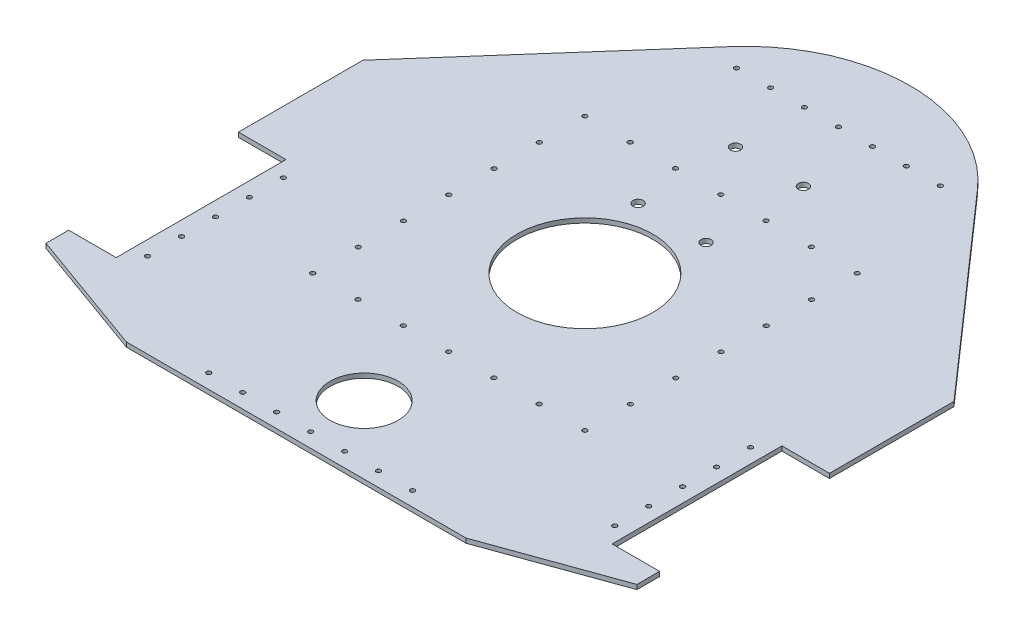
SolidWorks part; units mm, degrees
ref_plane "Front Plane" through (0, 0, 0) normal (0, 0, 1) x (1, 0, 0)
ref_plane "Top Plane" through (0, 0, 0) normal (0, 1, 0) x (1, 0, 0)
ref_plane "Right Plane" through (0, 0, 0) normal (1, 0, 0) x (0, 0, -1)
sketch "Sketch1" plane through (0, 0, 0) normal (0, 1, 0) x (1, 0, 0)
  line L0 (-240, -25) -> (240, -25) construction
  line L1 (240, -25) -> (0, 215) construction
  line L2 (0, 215) -> (-240, -25) construction
  line L3 (0, 215) -> (0, -25) construction
  line L6 (-219, 50) -> (-219, -100)
  line L7 (-219, -100) -> (-261, -100)
  line L8 (-261, -100) -> (-261, -120)
  line L10 (-150, -160) -> (150, -160)
  line L11 (-219, 50) -> (-261, 50)
  line L12 (-261, 50) -> (-261, 160)
  line L13 (-261, 160) -> (-110, 331.6587)
  line L14 (-150, -160) -> (-261, -120)
  line L15 (261, 160) -> (110, 331.6587)
  line L16 (150, -160) -> (261, -120)
  line L18 (261, -100) -> (261, -120)
  line L19 (219, -100) -> (261, -100)
  line L20 (219, 50) -> (219, -100)
  line L21 (219, 50) -> (261, 50)
  line L22 (261, 50) -> (261, 160)
  arc A7 (110, 331.6587) -> (-110, 331.6587) centre (0, 237.0979) ccw
  point P29 (0, 331.6587)
  dimension "D1" = 480
  dimension "D4" = 75
  dimension "D6" = 20
  dimension "D7" = 42
  dimension "D2" = 240
  dimension "D3" = 21
  dimension "D5" = 75
  dimension "D8" = 20
  dimension "D9" = 21
  dimension "D10" = 21
  dimension "D11" = 110
  dimension "D12" = 110
  dimension "D13" = 150
  dimension "D14" = 42
  dimension "D15" = 300
extrude "Boss-Extrude1" add sketch "Sketch1" along normal blind 4
sketch "Sketch2" plane through (0, 4, 0) normal (0, 1, 0) x (1, 0, 0)
  line L0 (-206.3, 24.3269) -> (-206.3, -74.3269) construction
  line L1 (-219, 50) -> (-219, -100) construction
  line L2 (0, 319.1541) -> (0, -121.9152) construction
  line L4 (-219, 50) -> (-261, 50) construction
  line L5 (219, 50) -> (261, 50) construction
  circle A0 centre (-206.3, -25) radius 2
  circle A1 centre (-206.3, 5) radius 2
  circle A2 centre (-206.3, 35) radius 2
  circle A3 centre (-206.3, -55) radius 2
  circle A4 centre (-206.3, -85) radius 2
  circle A6 centre (206.3, -85) radius 2
  circle A7 centre (206.3, -55) radius 2
  circle A8 centre (206.3, -25) radius 2
  circle A9 centre (206.3, 5) radius 2
  circle A10 centre (206.3, 35) radius 2
  dimension "D2" = 3
  dimension "D1" = 12.7
  dimension "D4" = 75
  dimension "D5" = 75
  dimension "D6" = 12.7
  dimension "D3" = 3
extrude "Cut-Extrude1" cut sketch "Sketch2" against normal up to surface (4 mm away) up to face at (0, 0, -17.1134)
sketch "Sketch4" plane through (0, 4, 0) normal (0, 1, 0) x (1, 0, 0)
  line L0 (0, 0) -> (0, -135) construction
  line L1 (-120.2082, 215.2082) -> (-120.2082, -25.2082) construction
  line L2 (-219, -25) -> (219, -25) construction
  line L7 (-219, 50) -> (-219, -100) construction
  line L8 (219, 50) -> (219, -100) construction
  line L9 (-150, -160) -> (150, -160) construction
  line L10 (0, 382.1556) -> (0, -160) construction
  line L11 (0, 95) -> (-120.2082, 215.2082) construction
  circle A5 centre (0, -100) radius 30
  arc A6 (110, 331.6587) -> (-110, 331.6587) centre (0, 237.0979) ccw construction
  circle A7 centre (-120.2082, 215.2082) radius 2
  circle A8 centre (0, 95) radius 60
  circle A9 centre (120.2082, 215.2082) radius 2
  circle A10 centre (120.2082, -25.2082) radius 2
  circle A11 centre (-120.2082, -25.2082) radius 2
  circle A12 centre (-120.2082, 95) radius 2
  circle A13 centre (-120.2082, 135) radius 2
  circle A14 centre (-120.2082, 175) radius 2
  circle A15 centre (-120.2082, 55) radius 2
  circle A16 centre (-120.2082, 15) radius 2
  circle A17 centre (120.2082, 15) radius 2
  circle A18 centre (120.2082, 55) radius 2
  circle A19 centre (120.2082, 95) radius 2
  circle A20 centre (120.2082, 135) radius 2
  circle A21 centre (120.2082, 175) radius 2
  circle A22 centre (-80.2082, 215.2082) radius 2
  circle A23 centre (-80.2082, -25.2082) radius 2
  circle A24 centre (-40.2082, 215.2082) radius 2
  circle A25 centre (-40.2082, -25.2082) radius 2
  circle A26 centre (-0.2082, 215.2082) radius 2
  circle A27 centre (-0.2082, -25.2082) radius 2
  circle A28 centre (39.7918, 215.2082) radius 2
  circle A29 centre (39.7918, -25.2082) radius 2
  circle A30 centre (79.7918, 215.2082) radius 2
  circle A31 centre (79.7918, -25.2082) radius 2
  point P31 (0, 95)
  dimension "D1" = 120
  dimension "D4" = 60
  dimension "D7" = 3
  dimension "D3" = 45
  dimension "D5" = 60
  dimension "D2" = 170
  dimension "D8" = 3
  dimension "D9" = 6
  dimension "D6" = 4
extrude "Cut-Extrude2" cut sketch "Sketch4" against normal up to surface (4 mm away) up to face at (-206.3, 0, -3)
sketch "Sketch5" plane through (0, 4, 0) normal (0, 1, 0) x (1, 0, 0)
  line L0 (-219, -25) -> (219, -25) construction
  line L1 (-219, 50) -> (-219, -100) construction
  line L2 (219, 50) -> (219, -100) construction
  line L3 (0, 0) -> (0, 215) construction
  circle A0 centre (-30, 172) radius 4.5
  circle A1 centre (30, 172) radius 4.5
  circle A2 centre (30, 258) radius 4.5
  circle A3 centre (-30, 258) radius 4.5
  dimension "D2" = 30
  dimension "D1" = 215
  dimension "D3" = 43
  dimension "D4" = 2
  dimension "D5" = 2
extrude "Cut-Extrude3" cut sketch "Sketch5" against normal up to surface (4 mm away) up to face at (-80.2082, 0, -213.2082)
sketch "Sketch6" plane through (0, 4, 0) normal (0, 1, 0) x (1, 0, 0)
  line L0 (-110, 331.6587) -> (110, 331.6587) construction
  line L1 (0, 331.6587) -> (0, 301.6408) construction
  line L2 (0, -135) -> (0, -101.3263) construction
  line L4 (-150, -160) -> (150, -160) construction
  circle A0 centre (0, 318.9587) radius 2
  circle A1 centre (30, 318.9587) radius 2
  circle A2 centre (60, 318.9587) radius 2
  circle A3 centre (90, 318.9587) radius 2
  circle A4 centre (-30, 318.9587) radius 2
  circle A5 centre (-60, 318.9587) radius 2
  circle A6 centre (-90, 318.9587) radius 2
  circle A7 centre (0, -147.3) radius 2
  circle A8 centre (30, -147.3) radius 2
  circle A9 centre (60, -147.3) radius 2
  circle A10 centre (90, -147.3) radius 2
  circle A11 centre (-30, -147.3) radius 2
  circle A12 centre (-60, -147.3) radius 2
  circle A13 centre (-90, -147.3) radius 2
  dimension "D1" = 12.7
  dimension "D4" = 12.7
  dimension "D2" = 4
  dimension "D3" = 4
  dimension "D5" = 4
  dimension "D6" = 4
extrude "Cut-Extrude4" cut sketch "Sketch6" against normal up to surface (4 mm away) up to face at (-30, 0, -253.5)
